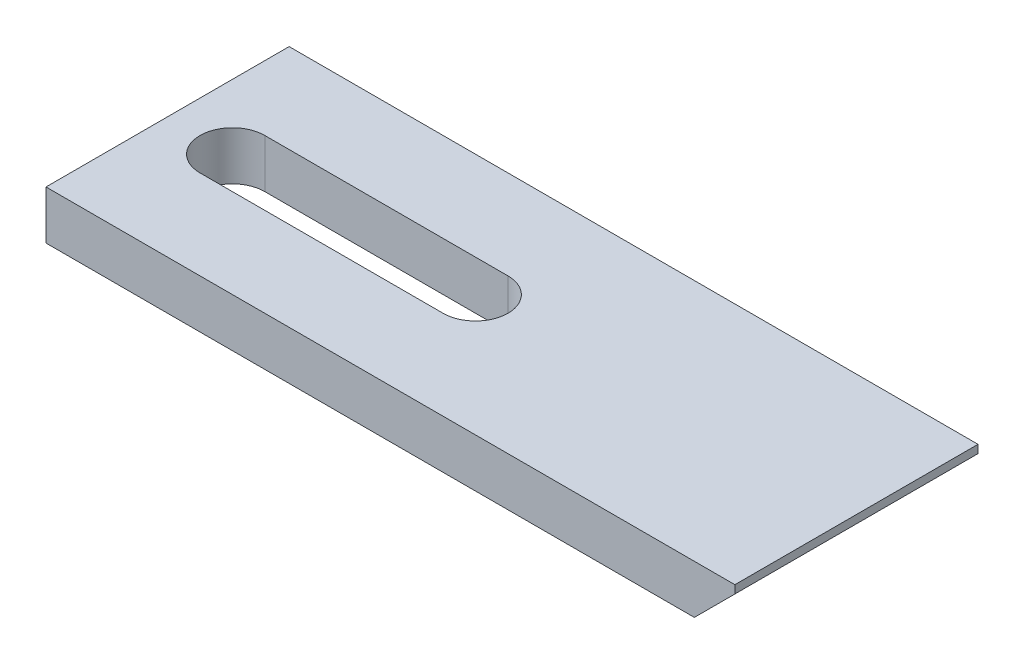
SolidWorks part; units mm, degrees
ref_plane "Спереди" through (0, 0, 0) normal (0, 0, 1) x (1, 0, 0)
ref_plane "Сверху" through (0, 0, 0) normal (0, 1, 0) x (1, 0, 0)
ref_plane "Справа" through (0, 0, 0) normal (1, 0, 0) x (0, 0, -1)
sketch "Эскиз1" plane through (0, 0, 0) normal (0, 1, 0) x (1, 0, 0)
  line L0 (-42.5, -15) -> (42.5, 15) construction
  line L1 (-42.5, 15) -> (42.5, 15)
  line L2 (-42.5, 15) -> (-42.5, -15)
  line L3 (-42.5, -15) -> (42.5, -15)
  line L4 (42.5, 15) -> (42.5, -15)
  line L5 (-34.5, 0) -> (-42.5, 0) construction
  line L6 (-34.5, 4) -> (-24.5, 4)
  line L7 (-34.5, -4) -> (-24.5, -4)
  line L8 (-19.5, 15) -> (-19.5, -15) construction
  line L9 (-4.5, 4) -> (-14.5, 4)
  line L10 (-4.5, -4) -> (-14.5, -4)
  arc A0 (-34.5, 4) -> (-34.5, -4) centre (-34.5, 0) ccw
  arc A1 (-24.5, -4) -> (-24.5, 4) centre (-24.5, 0) ccw
  arc A2 (-14.5, -4) -> (-14.5, 4) centre (-14.5, 0) cw
  arc A3 (-4.5, 4) -> (-4.5, -4) centre (-4.5, 0) cw
  dimension "D3" = 8
  dimension "D6" = 20
  dimension "D1" = 85
  dimension "D2" = 30
  dimension "D4" = 10
  dimension "D5" = 8
extrude "Бобышка-Вытянуть1" add sketch "Эскиз1" along normal blind 6
sketch "Эскиз2" plane through (0, 0, 15) normal (0, 0, 1) x (1, 0, 0)
  line L0 (42.5, 5) -> (37.5, 0)
  line L1 (42.5, 6) -> (42.5, 0) construction
  line L2 (-42.5, 0) -> (42.5, 0) construction
  line L3 (37.5, 0) -> (42.5, 0)
  line L4 (42.5, 0) -> (42.5, 5)
  dimension "D1" = 5
extrude "Вырез-Вытянуть1" cut sketch "Эскиз2" against normal through all
ref_plane "Плоскость1" through (-4.5, 0, 0) normal (-1, 0, 0) x (0, 0, 1)
sketch "Эскиз3" plane through (0, 6, 0) normal (0, 1, 0) x (1, 0, 0)
  line L0 (-4.5, 4) -> (-14.5, 4) construction
  line L1 (-24.5, -4) -> (-14.5, -4)
  line L2 (-24.5, -4) -> (-24.5, 4)
  line L3 (-24.5, 4) -> (-14.5, 4)
  line L4 (-14.5, -4) -> (-14.5, 4)
  arc A0 (-14.5, 4) -> (-14.5, -4) centre (-14.5, 0) ccw construction
extrude "Вырез-Вытянуть2" cut sketch "Эскиз3" against normal through all
